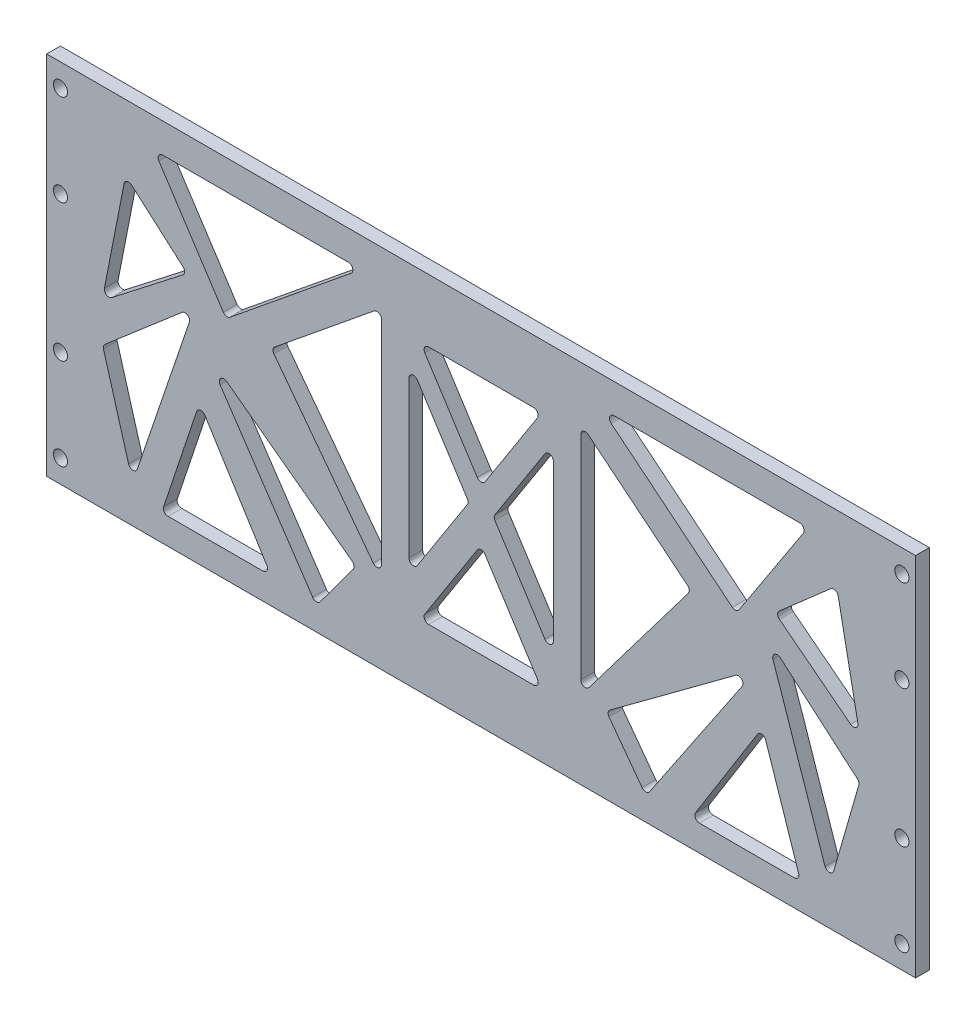
SolidWorks part; units mm, degrees
ref_plane "前视基准面" through (0, 0, 0) normal (0, 0, 1) x (1, 0, 0)
ref_plane "上视基准面" through (0, 0, 0) normal (0, 1, 0) x (1, 0, 0)
ref_plane "右视基准面" through (0, 0, 0) normal (1, 0, 0) x (0, 0, -1)
sketch "草图1" plane through (0, 0, 0) normal (0, 0, 1) x (1, 0, 0)
  line L1 (-95, 40) -> (95, 40)
  line L2 (-95, 40) -> (-95, -40)
  line L3 (-95, -40) -> (95, -40)
  line L4 (95, 40) -> (95, -40)
  line L5 (-95, 40) -> (95, -40) construction
  line L6 (-95, -40) -> (95, 40) construction
  point P0 (0, 0)
  dimension "D1" = 190
  dimension "D2" = 80
extrude "凸台-拉伸1" add sketch "草图1" along normal blind 3
sketch "草图2" plane through (0, 0, 3) normal (0, 0, 1) x (1, 0, 0)
  line L0 (-95, 40) -> (-92, 40) construction
  line L1 (95, 40) -> (-95, 40) construction
  line L2 (-92, 40) -> (-92, 35) construction
  circle A0 centre (-92, 35) radius 1.55
  circle A1 centre (-92, 15) radius 1.55
  circle A2 centre (-92, -15) radius 1.55
  circle A3 centre (-92, -35) radius 1.55
  dimension "D3" = 3.1
  dimension "D1" = 3
  dimension "D2" = 5
  dimension "D4" = 2
  dimension "D5" = 2
  dimension "D6" = 2
extrude "切除-拉伸1" cut sketch "草图2" against normal blind 3
mirror "镜向1" about plane through (0, 0, 0) normal (1, 0, 0) of "切除-拉伸1"
sketch "草图3" plane through (0, 0, 3) normal (0, 0, 1) x (1, 0, 0)
  line L0 (-13.3051, 26.2758) -> (13.3051, 26.2758)
  line L1 (-18.7964, 29.2758) -> (18.7964, 29.2758)
  line L2 (-18.7964, 29.2758) -> (-18.7964, -29.2758)
  line L3 (-18.7964, -29.2758) -> (18.7964, -29.2758)
  line L4 (18.7964, 29.2758) -> (18.7964, -29.2758)
  line L5 (-18.7964, 29.2758) -> (18.7964, -29.2758) construction
  line L6 (-18.7964, -29.2758) -> (18.7964, 29.2758) construction
  line L7 (13.3051, 26.2758) -> (0, 5.5527)
  line L8 (0, 5.5527) -> (-13.3051, 26.2758)
  line L9 (95, 40) -> (-95, 40) construction
  line L10 (0, 0) -> (50.6776, 0) construction
  line L11 (0, 0) -> (0, 68.0732) construction
  line L12 (-15.7964, 21.6459) -> (-15.7964, -19.2386)
  line L13 (-15.7964, -19.2386) -> (-2.6715, 1.2036)
  line L14 (-2.6715, 1.2036) -> (-15.7964, 21.6459)
  line L15 (13.3051, -26.2758) -> (0, -5.5527)
  line L16 (-13.3051, -26.2758) -> (13.3051, -26.2758)
  line L17 (0, -5.5527) -> (-13.3051, -26.2758)
  line L18 (15.7964, -19.2386) -> (2.6715, 1.2036)
  line L19 (15.7964, 21.6459) -> (15.7964, -19.2386)
  line L20 (2.6715, 1.2036) -> (15.7964, 21.6459)
  point P0 (0, 0)
  dimension "D1" = 3
  dimension "D2" = 3
  dimension "D3" = 3
extrude "切除-拉伸3" cut sketch "草图3" against normal blind 3 contours L8 L0 L7 | L14 L12 L13 | L15 L17 L16 | L18 L20 L19
fillet "圆角1" radius 1 12 edges at (-15.7964, -19.2386, 1.5) (-2.6715, 1.2036, 1.5) (-15.7964, 21.6459, 1.5) (0, -5.5527, 1.5) (13.3051, -26.2758, 1.5) (-13.3051, -26.2758, 1.5) (15.7964, -19.2386, 1.5) (2.6715, 1.2036, 1.5) (15.7964, 21.6459, 1.5) (13.3051, 26.2758, 1.5) (0, 5.5527, 1.5) (-13.3051, 26.2758, 1.5)
sketch "草图4" plane through (0, 0, 3) normal (0, 0, 1) x (1, 0, 0)
  line L0 (-77.7457, 25.5946) -> (-82.9023, -0.6871)
  line L1 (-82.9023, -0.6871) -> (-64.2722, 13.7845)
  line L2 (-64.2722, 13.7845) -> (-77.7457, 25.5946)
  line L3 (-71.4755, 33.5283) -> (-26.2455, 33.5283)
  line L4 (-26.2455, 33.5283) -> (-55.7817, 9.4741)
  line L5 (-55.7817, 9.4741) -> (-71.4755, 33.5283)
  line L6 (-62.6378, 8.2374) -> (-82.7649, -9.0619)
  line L7 (-82.7649, -9.0619) -> (-76.2176, -31.7535)
  line L8 (-76.2176, -31.7535) -> (-62.6378, 8.2374)
  line L9 (-60.3235, 1.1138) -> (-27.3724, -23.2737)
  line L10 (-27.3724, -23.2737) -> (-36.0379, -34.982)
  line L11 (-36.0379, -34.982) -> (-60.3235, 1.1138)
  line L12 (-61.5529, -9.3211) -> (-69.8675, -34.2949)
  line L13 (-69.8675, -34.2949) -> (-45.917, -34.2949)
  line L14 (-45.917, -34.2949) -> (-61.5529, -9.3211)
  line L15 (-45.8977, 8.8065) -> (-21.7848, 28.444)
  line L16 (-21.7848, 28.444) -> (-21.7848, -23.0852)
  line L17 (-21.7848, -23.0852) -> (-45.8977, 8.8065)
  point P17 (-30.6427, 30.5053)
extrude "切除-拉伸4" cut sketch "草图4" against normal blind 3
fillet "圆角2" radius 1 18 edges at (-21.7848, -23.0852, 1.5) (-45.8977, 8.8065, 1.5) (-21.7848, 28.444, 1.5) (-76.2176, -31.7535, 1.5) (-62.6378, 8.2374, 1.5) (-82.7649, -9.0619, 1.5) (-69.8675, -34.2949, 1.5) (-61.5529, -9.3211, 1.5) (-45.917, -34.2949, 1.5) (-60.3235, 1.1138, 1.5) (-36.0379, -34.982, 1.5) (-27.3724, -23.2737, 1.5) (-26.2455, 33.5283, 1.5) (-71.4755, 33.5283, 1.5) (-55.7817, 9.4741, 1.5) (-64.2722, 13.7845, 1.5) (-77.7457, 25.5946, 1.5) (-82.9023, -0.6871, 1.5)
mirror "镜向2" about plane through (0, 0, 0) normal (1, 0, 0) of "圆角2", "切除-拉伸4"
